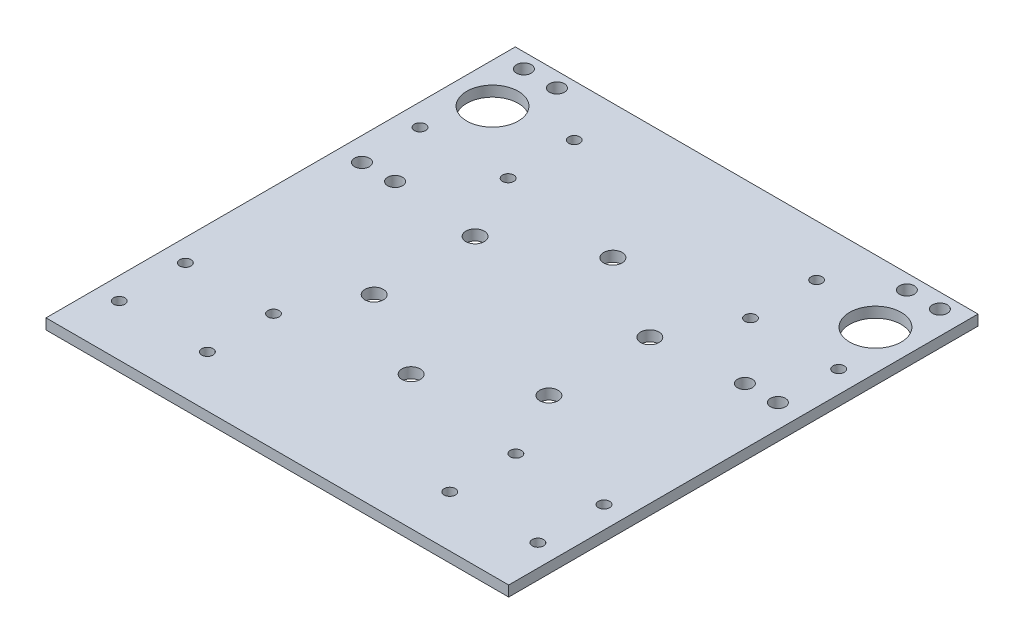
SolidWorks part; units mm, degrees
ref_plane "Front Plane" through (0, 0, 0) normal (0, 0, 1) x (1, 0, 0)
ref_plane "Top Plane" through (0, 0, 0) normal (0, 1, 0) x (1, 0, 0)
ref_plane "Right Plane" through (0, 0, 0) normal (1, 0, 0) x (0, 0, -1)
sketch "Sketch1" plane through (0, 0, 0) normal (0, 1, 0) x (1, 0, 0)
  line L1 (-70, -71) -> (70, -71)
  line L2 (-70, -71) -> (-70, 71)
  line L3 (-70, 71) -> (70, 71)
  line L4 (70, -71) -> (70, 71)
  line L5 (-70, -71) -> (70, 71) construction
  line L6 (-70, 71) -> (70, -71) construction
  point P0 (0, 0)
  dimension "D1" = 140
  dimension "D2" = 142
extrude "Boss-Extrude1" add sketch "Sketch1" along normal blind 3.175
sketch "Sketch2" plane through (0, 3.175, 0) normal (0, 1, 0) x (1, 0, 0)
  line L0 (-45, 30.5) -> (-30, 30.5) construction
  line L1 (-45, -30.5) -> (45, -30.5) construction
  line L2 (-45, -30.5) -> (-45, 30.5) construction
  line L3 (-45, 30.5) -> (45, 30.5) construction
  line L4 (45, -30.5) -> (45, 30.5) construction
  line L5 (-45, -30.5) -> (45, 30.5) construction
  line L6 (-45, 30.5) -> (45, -30.5) construction
  line L7 (-30, 30.5) -> (-30, 60.5) construction
  line L8 (-70, 71) -> (-70, -71) construction
  line L9 (-30, 60.5) -> (-70, 60.5) construction
  line L10 (-30, 60.5) -> (-30, 30.5) construction
  line L11 (-30, 30.5) -> (-70, 30.5) construction
  line L12 (-70, 60.5) -> (-70, 30.5) construction
  line L13 (-30, 60.5) -> (-70, 30.5) construction
  line L14 (-30, 30.5) -> (-70, 60.5) construction
  line L15 (-51.4643, -23.9643) -> (-51.4643, 60.5) construction
  line L16 (-70, 45.5) -> (-30, 45.5) construction
  line L17 (-50, 60.5) -> (-50, 30.5) construction
  line L18 (-57.9286, 52.0357) -> (-57.9286, 62.0357) construction
  line L19 (-62.9286, 66.5357) -> (-52.9286, 66.5357) construction
  line L20 (-67.9286, 62.0357) -> (-47.9286, 62.0357) construction
  line L21 (-67.9286, 62.0357) -> (-67.9286, 22.0357) construction
  line L22 (-67.9286, 22.0357) -> (-47.9286, 22.0357) construction
  line L23 (-47.9286, 62.0357) -> (-47.9286, 22.0357) construction
  line L24 (-67.9286, 62.0357) -> (-47.9286, 22.0357) construction
  line L25 (-67.9286, 22.0357) -> (-47.9286, 62.0357) construction
  line L26 (-67.9286, 17.5357) -> (-47.9286, 17.5357) construction
  line L27 (-67.9286, 17.5357) -> (-67.9286, 66.5357) construction
  line L28 (-67.9286, 66.5357) -> (-47.9286, 66.5357) construction
  line L29 (-47.9286, 17.5357) -> (-47.9286, 66.5357) construction
  line L30 (-67.9286, 17.5357) -> (-47.9286, 66.5357) construction
  line L31 (-67.9286, 66.5357) -> (-47.9286, 17.5357) construction
  line L32 (-67.9286, 14.0357) -> (-47.9286, 14.0357) construction
  line L33 (-67.9286, 14.0357) -> (-67.9286, 70.0357) construction
  line L34 (-67.9286, 70.0357) -> (-47.9286, 70.0357) construction
  line L35 (-47.9286, 14.0357) -> (-47.9286, 70.0357) construction
  line L36 (-67.9286, 14.0357) -> (-47.9286, 70.0357) construction
  line L37 (-67.9286, 70.0357) -> (-47.9286, 14.0357) construction
  line L38 (-67.9286, 42.0357) -> (-47.9286, 42.0357) construction
  line L39 (0, -1.7463) -> (0, 1.7463) construction
  line L40 (-45, 30.5) -> (-45, 45.5) construction
  line L41 (-1.7463, 0) -> (1.7463, 0) construction
  line L42 (-67.9286, 52.0357) -> (-30, 52.0357) construction
  circle A0 centre (-45, 0) radius 6.4643 construction
  circle A1 centre (-57.9286, 52.0357) radius 6.4643 construction
  circle A2 centre (-57.9286, 52.0357) radius 7.8
  circle A8 centre (-57.9286, 52.0357) radius 2.45 construction
  circle A9 centre (-62.9286, 66.5357) radius 2.25
  circle A10 centre (-52.9286, 66.5357) radius 2.25
  circle A11 centre (-52.9286, 17.5357) radius 2.25
  circle A12 centre (-62.9286, 17.5357) radius 2.25
  circle A13 centre (52.9286, 17.5357) radius 2.25
  circle A14 centre (62.9286, 17.5357) radius 2.25
  circle A15 centre (57.9286, 52.0357) radius 7.8
  circle A16 centre (52.9286, 66.5357) radius 2.25
  circle A17 centre (62.9286, 66.5357) radius 2.25
  circle A18 centre (-36.6667, 55.5) radius 1.7
  circle A19 centre (-36.6667, 35.5) radius 1.7
  circle A20 centre (-63.3333, 35.5) radius 1.7
  circle A21 centre (-63.3333, 55.5) radius 1.7 construction
  circle A22 centre (36.6667, 35.5) radius 1.7
  circle A23 centre (63.3333, 35.5) radius 1.7
  circle A24 centre (36.6667, 55.5) radius 1.7
  circle A25 centre (63.3333, 55.5) radius 1.7 construction
  circle A26 centre (63.3333, -35.5) radius 1.7
  circle A27 centre (36.6667, -35.5) radius 1.7
  circle A28 centre (63.3333, -55.5) radius 1.7
  circle A29 centre (36.6667, -55.5) radius 1.7
  circle A30 centre (-36.6667, -35.5) radius 1.7
  circle A31 centre (-63.3333, -35.5) radius 1.7
  circle A32 centre (-36.6667, -55.5) radius 1.7
  circle A33 centre (-63.3333, -55.5) radius 1.7
  point P0 (0, 0)
  point P10 (-50, 45.5)
  point P25 (-57.9286, 42.0357)
  point P31 (-57.9286, 42.0357)
  point P32 (-57.9286, 62.0357)
  point P37 (-57.9286, 42.0357)
  point P44 (-57.9286, 66.5357)
  point P45 (-57.9286, 66.5357)
  dimension "D5" = 12.9286
  dimension "D6" = 12.9286
  dimension "D7" = 15.6
  dimension "D8" = 4.9
  dimension "D14" = 10
  dimension "D9" = 10
  dimension "4.5" = 4.5
  dimension "D16" = 3.4
  dimension "D1" = 90
  dimension "D2" = 61
  dimension "D3" = 15
  dimension "D4" = 30
  dimension "D10" = 20
  dimension "D11" = 40
  dimension "D12" = 49
  dimension "D13" = 56
  dimension "D17" = 5
  dimension "D18" = 8.4643
sketch "Sketch4" plane through (0, 3.175, 0) normal (0, 1, 0) x (1, 0, 0)
  line L0 (0, 0) -> (0, 30.525) construction
  line L1 (0, 0) -> (26.4354, 15.2625) construction
  circle A0 centre (0, 0) radius 40 construction
  circle A1 centre (0, 0) radius 30.525 construction
  circle A2 centre (0, 30.525) radius 2.7781
  circle A3 centre (26.4354, 15.2625) radius 2.7781
  circle A4 centre (26.4354, -15.2625) radius 2.7781
  circle A5 centre (0, -30.525) radius 2.7781
  circle A6 centre (-26.4354, -15.2625) radius 2.7781
  circle A7 centre (-26.4354, 15.2625) radius 2.7781
  dimension "D1" = 80
  dimension "D2" = 61.05
  dimension "D3" = 5.5563
  dimension "D5" = 60
  dimension "D4" = 6
extrude "Cut-Extrude1" cut sketch "Sketch2" against normal up to surface (3.175 mm away) contours A9 | A10 | A18 | A2 | A19 | A20 | A11 | A12 | A16 | A17 | A24 | A15 | A23 | A22 | A13 | A14 | A31 | A30 | A33 | A32 | A27 | A26 | A29 | A28 up to face at (0, 0, 0)
extrude "Cut-Extrude2" cut sketch "Sketch4" against normal up to surface (3.175 mm away) contours A7 | A2 | A3 | A6 | A4 | A5 up to face at (57.9286, 0, -59.8357)
